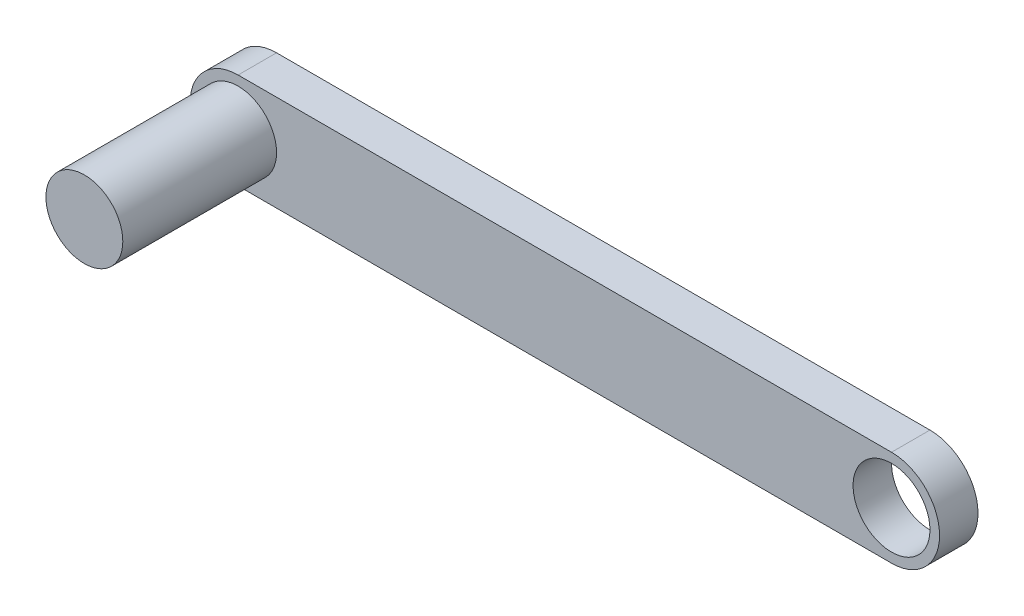
SolidWorks part; units mm, degrees
ref_plane "Front Plane" through (0, 0, 0) normal (0, 0, 1) x (1, 0, 0)
ref_plane "Top Plane" through (0, 0, 0) normal (0, 1, 0) x (1, 0, 0)
ref_plane "Right Plane" through (0, 0, 0) normal (1, 0, 0) x (0, 0, -1)
sketch "Sketch1" plane through (0, 0, 0) normal (0, 0, 1) x (1, 0, 0)
  line L0 (0, -2.5) -> (34, -2.5)
  line L3 (0, 2.5) -> (34, 2.5)
  arc A0 (0, 2.5) -> (0, -2.5) centre (0, 0) ccw
  arc A1 (34, -2.5) -> (34, 2.5) centre (34, 0) ccw
  dimension "D2" = 5
  dimension "D1" = 34
extrude "Boss-Extrude1" add sketch "Sketch1" along normal blind 2
sketch "Sketch2" plane through (0, 0, 2) normal (0, 0, 1) x (1, 0, 0)
  circle A0 centre (0, 0) radius 2
  dimension "D1" = 4
extrude "Boss-Extrude2" add sketch "Sketch2" along normal blind 8
sketch "Sketch5" plane through (0, 0, 0) normal (0, 0, -1) x (-1, 0, 0)
  circle A0 centre (-34, 0) radius 2
  dimension "D1" = 4
extrude "Cut-Extrude2" cut sketch "Sketch5" against normal mid plane 8
